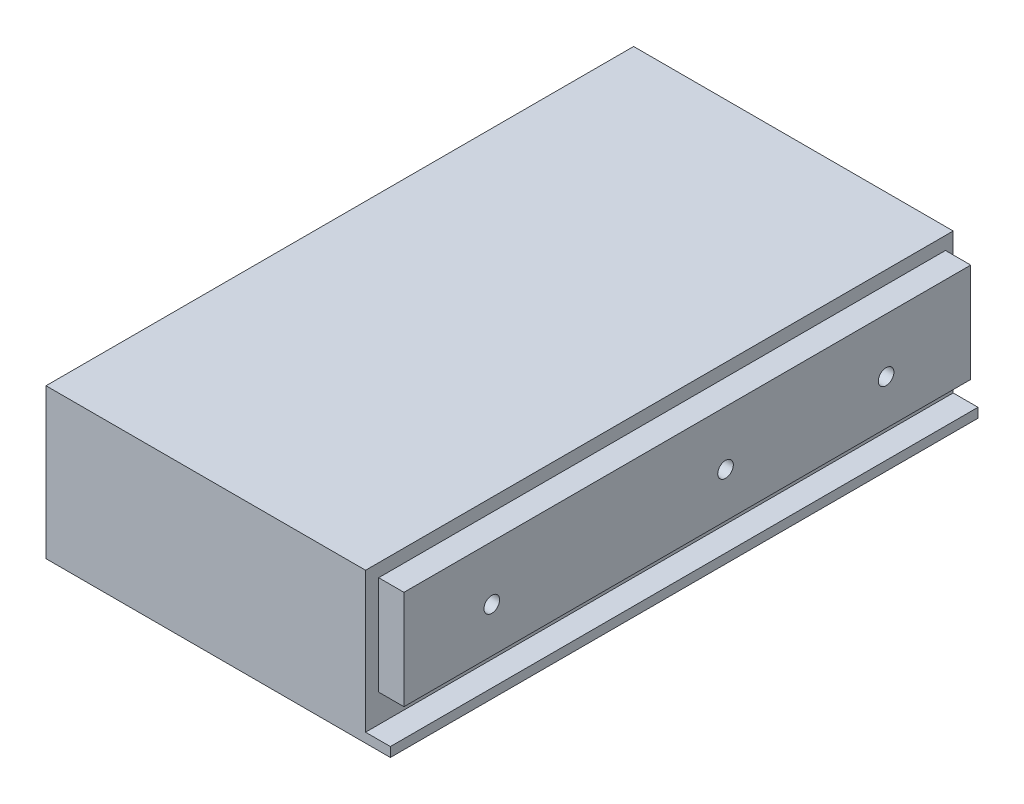
SolidWorks part; units mm, degrees
ref_plane "Front Plane" through (0, 0, 0) normal (0, 0, 1) x (1, 0, 0)
ref_plane "Top Plane" through (0, 0, 0) normal (0, 1, 0) x (1, 0, 0)
ref_plane "Right Plane" through (0, 0, 0) normal (1, 0, 0) x (0, 0, -1)
sketch "Sketch1" plane through (0, 0, 0) normal (0, 0, 1) x (1, 0, 0)
  line L0 (-28.0289, 0) -> (28.0289, 0)
  line L1 (28.0289, 0) -> (28.0289, 1.5494)
  line L2 (28.0289, 1.5494) -> (23.9903, 1.5494)
  line L3 (23.9903, 1.5494) -> (23.9903, 24.384)
  line L4 (23.9903, 24.384) -> (-28.0289, 24.384)
  line L5 (-28.0289, 24.384) -> (-28.0289, 0)
  dimension "D1" = 4.0386
  dimension "D2" = 1.5494
  dimension "D3" = 56.0578
  dimension "D4" = 24.384
extrude "Boss-Extrude1" add sketch "Sketch1" along normal blind 95.6564
sketch "Sketch2" plane through (23.9903, 0, 0) normal (1, 0, 0) x (0, 0, -1)
  line L1 (-93.5228, 22.2631) -> (-1.2573, 22.2631)
  line L2 (-93.5228, 22.2631) -> (-93.5228, 6.1341)
  line L3 (-93.5228, 6.1341) -> (-1.2573, 6.1341)
  line L4 (-1.2573, 22.2631) -> (-1.2573, 6.1341)
  line L6 (-95.6564, 24.384) -> (0, 24.384) construction
  line L7 (-95.6564, 1.5494) -> (-95.6564, 24.384) construction
  line L8 (0, 1.5494) -> (0, 24.384) construction
  circle A0 centre (-79.2226, 13.4239) radius 1.27
  circle A1 centre (-41.1734, 13.4239) radius 1.27
  circle A2 centre (-15.0368, 13.4239) radius 1.27
  dimension "D4" = 2.54
  dimension "D7" = 64.1858
  dimension "D1" = 2.1209
  dimension "D2" = 16.129
  dimension "D3" = 13.7795
  dimension "D5" = 8.8392
  dimension "D6" = 26.1366
  dimension "D8" = 2.1336
  dimension "D9" = 1.2573
extrude "Boss-Extrude2" add sketch "Sketch2" along normal blind 4.1148
